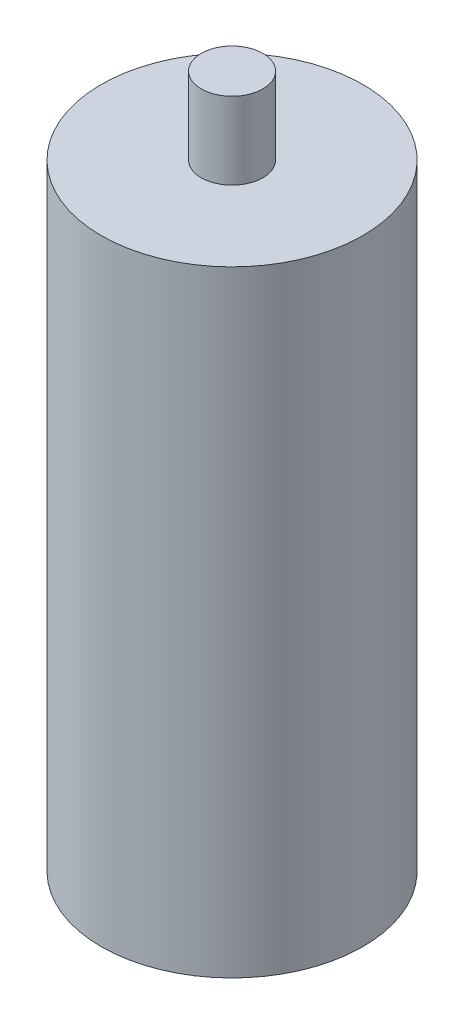
SolidWorks part; units mm, degrees
ref_plane "前视基准面" through (0, 0, 0) normal (0, 0, 1) x (1, 0, 0)
ref_plane "上视基准面" through (0, 0, 0) normal (0, 1, 0) x (1, 0, 0)
ref_plane "右视基准面" through (0, 0, 0) normal (1, 0, 0) x (0, 0, -1)
sketch "草图1" plane through (0, 0, 0) normal (0, 1, 0) x (1, 0, 0)
  circle A0 centre (0, 0) radius 17
extrude "凸台-拉伸1" add sketch "草图1" along normal blind 80
sketch "草图2" plane through (0, 80, 0) normal (0, 1, 0) x (1, 0, 0)
  circle A0 centre (0, 0) radius 4
extrude "凸台-拉伸2" add sketch "草图2" along normal blind 10
